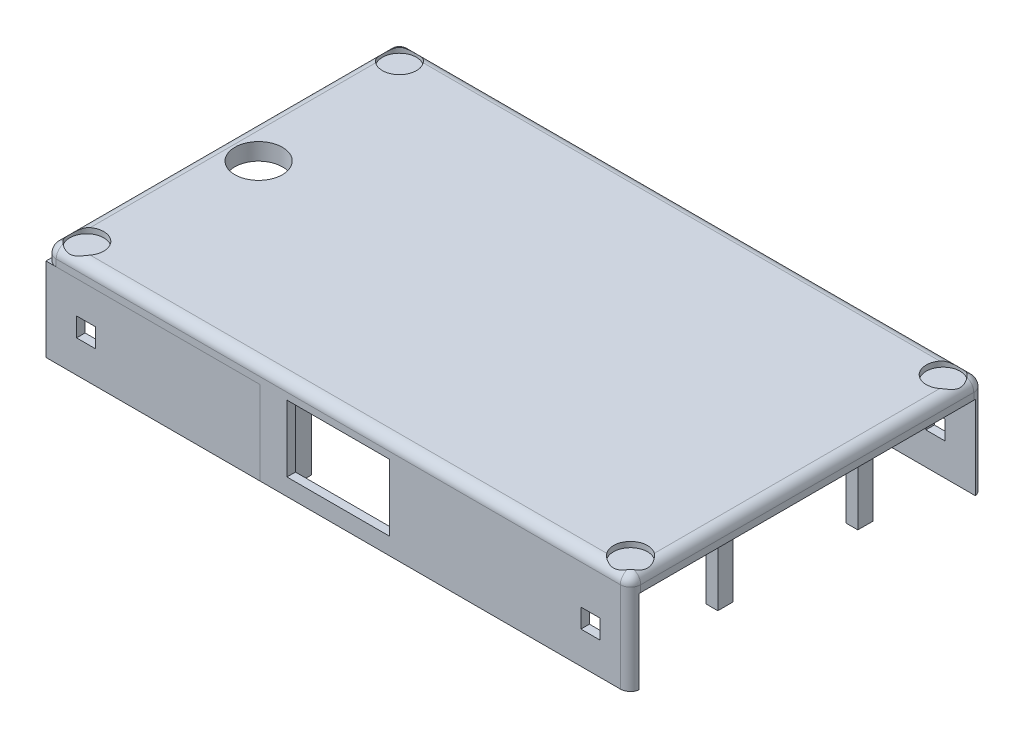
SolidWorks part; units mm, degrees
ref_plane "Plano frontal" through (0, 0, 0) normal (0, 0, 1) x (1, 0, 0)
ref_plane "Plano superior" through (0, 0, 0) normal (0, 1, 0) x (1, 0, 0)
ref_plane "Plano direito" through (0, 0, 0) normal (1, 0, 0) x (0, 0, -1)
sketch "Esboço1" plane through (0, 0, 0) normal (0, 1, 0) x (1, 0, 0)
  line L1 (-102.6129, 52.2382) -> (69.3871, 52.2382)
  line L2 (-102.6129, 52.2382) -> (-102.6129, -51.7618)
  line L3 (-102.6129, -51.7618) -> (69.3871, -51.7618)
  line L4 (69.3871, 52.2382) -> (69.3871, -51.7618)
extrude "Ressalto-extrusão1" add sketch "Esboço1" along normal blind 5
sketch "Esboço6" plane through (0, 0, 51.7618) normal (0, 0, 1) x (1, 0, 0)
  line L1 (-102.6129, 0) -> (-39.6029, 0)
  line L2 (-102.6129, 0) -> (-102.6129, -24.6)
  line L3 (-102.6129, -24.6) -> (-39.6029, -24.6)
  line L4 (-39.6029, 0) -> (-39.6029, -24.6)
extrude "Ressalto-extrusão3" add sketch "Esboço6" against normal blind 2.5 separate body
sketch "Esboço9" plane through (0, 0, 49.2618) normal (0, 0, -1) x (-1, 0, 0)
  line L1 (93.6129, -9.5) -> (88.0129, -9.5)
  line L2 (93.6129, -9.5) -> (93.6129, -15.1)
  line L3 (93.6129, -15.1) -> (88.0129, -15.1)
  line L4 (88.0129, -9.5) -> (88.0129, -15.1)
  line L6 (39.6029, 0) -> (102.6129, 0) construction
  line L7 (102.6129, -24.6) -> (39.6029, -24.6) construction
  line L8 (102.6129, 0) -> (102.6129, -24.6) construction
  dimension "D1" = 9.5
  dimension "D2" = 9
  dimension "D3" = 9.5
extrude "Corte-extrusão1" cut sketch "Esboço9" against normal blind 5
sketch "Esboço10" plane through (0, 0, -52.2382) normal (0, 0, -1) x (-1, 0, 0)
  line L1 (102.6129, 0) -> (39.6129, 0)
  line L2 (102.6129, 0) -> (102.6129, -24.6)
  line L3 (102.6129, -24.6) -> (39.6129, -24.6)
  line L4 (39.6129, 0) -> (39.6129, -24.6)
extrude "Ressalto-extrusão4" add sketch "Esboço10" against normal blind 2.5 separate body
sketch "Esboço11" plane through (0, 0, -49.7382) normal (0, 0, 1) x (1, 0, 0)
  line L1 (-102.6129, 0) -> (69.3871, 0) construction
  line L2 (-88.0129, -15.1) -> (-93.6129, -15.1)
  line L3 (-88.0129, -15.1) -> (-88.0129, -9.5)
  line L4 (-88.0129, -9.5) -> (-93.6129, -9.5)
  line L14 (-102.6129, -24.6) -> (-102.6129, 0) construction
  line L15 (-93.6129, -15.1) -> (-93.6129, -9.5)
  line L16 (-39.6129, -24.6) -> (-102.6129, -24.6) construction
  dimension "D1" = 9
  dimension "D2" = 9.5
  dimension "D3" = 9.5
extrude "Corte-extrusão2" cut sketch "Esboço11" against normal blind 5
sketch "Esboço12" plane through (0, 0, -52.2382) normal (0, 0, -1) x (-1, 0, 0)
  line L1 (-69.3871, 0) -> (-6.3871, 0)
  line L2 (-69.3871, 0) -> (-69.3871, -24.6)
  line L3 (-69.3871, -24.6) -> (-6.3871, -24.6)
  line L4 (-6.3871, 0) -> (-6.3871, -24.6)
extrude "Ressalto-extrusão5" add sketch "Esboço12" against normal blind 2.5 separate body
sketch "Esboço15" plane through (0, 0, 51.7618) normal (0, 0, 1) x (1, 0, 0)
  line L1 (69.3871, 0) -> (6.3871, 0)
  line L2 (69.3871, 0) -> (69.3871, -24.6)
  line L3 (69.3871, -24.6) -> (6.3871, -24.6)
  line L4 (6.3871, 0) -> (6.3871, -24.6)
extrude "Ressalto-extrusão6" add sketch "Esboço15" against normal blind 2.5 separate body
sketch "Esboço18" plane through (0, 0, -52.2382) normal (0, 0, -1) x (-1, 0, 0)
  line L0 (-69.3871, -24.6) -> (-6.3871, -24.6) construction
  line L1 (-54.7871, -15.1) -> (-60.3871, -15.1)
  line L2 (-54.7871, -15.1) -> (-54.7871, -9.5)
  line L3 (-54.7871, -9.5) -> (-60.3871, -9.5)
  line L4 (-60.3871, -15.1) -> (-60.3871, -9.5)
  line L5 (-6.3871, 0) -> (-69.3871, 0) construction
  line L6 (-69.3871, 0) -> (-69.3871, -24.6) construction
  dimension "D1" = 9.5
  dimension "D2" = 9.5
  dimension "D3" = 9
extrude "Corte-extrusão5" cut sketch "Esboço18" against normal blind 10
sketch "Esboço19" plane through (0, 0, 51.7618) normal (0, 0, 1) x (1, 0, 0)
  line L1 (60.3871, -15.1) -> (54.7871, -15.1)
  line L2 (60.3871, -15.1) -> (60.3871, -9.5)
  line L3 (60.3871, -9.5) -> (54.7871, -9.5)
  line L4 (54.7871, -15.1) -> (54.7871, -9.5)
  line L5 (69.3871, 0) -> (6.3871, 0) construction
  line L6 (6.3871, -24.6) -> (69.3871, -24.6) construction
  line L7 (69.3871, -24.6) -> (69.3871, 0) construction
  point P4 (57.5871, -9.5)
  dimension "D1" = 9.5
  dimension "D2" = 9.5
  dimension "D3" = 9
extrude "Corte-extrusão6" cut sketch "Esboço19" against normal blind 10
sketch "Esboço20" plane through (0, 0, 51.7618) normal (0, 0, 1) x (1, 0, 0)
  line L1 (6.3871, 0) -> (-1.5129, 0)
  line L2 (6.3871, 0) -> (6.3871, -24.6)
  line L3 (6.3871, -24.6) -> (-1.5129, -24.6)
  line L4 (-1.5129, 0) -> (-1.5129, -24.6)
extrude "Ressalto-extrusão7" add sketch "Esboço20" against normal blind 2.5
sketch "Esboço21" plane through (0, 0, 51.7618) normal (0, 0, 1) x (1, 0, 0)
  line L1 (-39.6029, 0) -> (-31.7129, 0)
  line L2 (-39.6029, 0) -> (-39.6029, -24.6)
  line L3 (-39.6029, -24.6) -> (-31.7129, -24.6)
  line L4 (-31.7129, 0) -> (-31.7129, -24.6)
extrude "Ressalto-extrusão8" add sketch "Esboço21" against normal blind 2.5 separate body
sketch "Esboço25" plane through (0, 0, 0) normal (0, -1, 0) x (1, 0, 0)
  line L0 (69.3871, 49.2618) -> (-1.5129, 49.2618) construction
  line L2 (4.3071, 49.2618) -> (0.3871, 49.2618)
  line L3 (4.3071, 49.2618) -> (4.3071, 42.6618)
  line L4 (4.3071, 42.6618) -> (0.3871, 42.6618)
  line L5 (0.3871, 49.2618) -> (0.3871, 42.6618)
  dimension "D1" = 1.9
extrude "Ressalto-extrusão9" add sketch "Esboço25" along normal blind 24.6
sketch "Esboço27" plane through (0, 0, 0) normal (0, -1, 0) x (1, 0, 0)
  line L0 (-31.7129, 49.2618) -> (-39.6029, 49.2618) construction
  line L1 (-37.5329, 42.6618) -> (-33.6129, 42.6618)
  line L2 (-37.5329, 42.6618) -> (-37.5329, 49.2618)
  line L3 (-37.5329, 49.2618) -> (-33.6129, 49.2618)
  line L4 (-33.6129, 42.6618) -> (-33.6129, 49.2618)
  line L6 (-31.7129, 49.2618) -> (-31.7129, 51.7618) construction
  dimension "D1" = 0
  dimension "D2" = 1.9
extrude "Ressalto-extrusão10" add sketch "Esboço27" along normal blind 24.6
sketch "Esboço28" plane through (-31.7129, 0, 0) normal (1, 0, 0) x (0, 0, -1)
  line L0 (-51.7618, -24.6) -> (-51.7618, 0) construction
  line L1 (-49.2618, -24.6) -> (-51.7618, -24.6)
  line L2 (-49.2618, -24.6) -> (-49.2618, -19.6)
  line L3 (-49.2618, -19.6) -> (-51.7618, -19.6)
  line L4 (-51.7618, -24.6) -> (-51.7618, -19.6)
extrude "Ressalto-extrusão11" add sketch "Esboço28" along normal blind 30.6
sketch "Esboço29" plane through (0, 0, -52.2382) normal (0, 0, -1) x (-1, 0, 0)
  line L0 (-69.3871, 0) -> (102.6129, 0) construction
  line L1 (39.6129, -24.6) -> (31.7129, -24.6)
  line L2 (39.6129, -24.6) -> (39.6129, 0)
  line L3 (39.6129, 0) -> (31.7129, 0)
  line L4 (31.7129, -24.6) -> (31.7129, 0)
extrude "Ressalto-extrusão12" add sketch "Esboço29" against normal blind 2.5
sketch "Esboço30" plane through (0, 0, -52.2382) normal (0, 0, -1) x (-1, 0, 0)
  line L0 (-6.3871, -24.6) -> (-6.3871, 0) construction
  line L1 (-6.3871, -24.6) -> (1.5129, -24.6)
  line L2 (-6.3871, -24.6) -> (-6.3871, 0)
  line L3 (-6.3871, 0) -> (1.5129, 0)
  line L4 (1.5129, -24.6) -> (1.5129, 0)
  line L5 (-69.3871, 0) -> (31.7129, 0) construction
extrude "Ressalto-extrusão13" add sketch "Esboço30" against normal blind 2.5
sketch "Esboço31" plane through (0, 0, 0) normal (0, -1, 0) x (1, 0, 0)
  line L0 (-102.6129, -49.7382) -> (-31.7129, -49.7382) construction
  line L1 (-37.5329, -49.7382) -> (-33.6129, -49.7382)
  line L2 (-37.5329, -49.7382) -> (-37.5329, -43.1382)
  line L3 (-37.5329, -43.1382) -> (-33.6129, -43.1382)
  line L4 (-33.6129, -49.7382) -> (-33.6129, -43.1382)
  dimension "D1" = 1.9
extrude "Ressalto-extrusão14" add sketch "Esboço31" along normal blind 24.6
sketch "Esboço32" plane through (0, 0, 0) normal (0, -1, 0) x (1, 0, 0)
  line L0 (-1.5129, -49.7382) -> (69.3871, -49.7382) construction
  line L1 (4.3071, -49.7382) -> (0.3871, -49.7382)
  line L2 (4.3071, -49.7382) -> (4.3071, -45.6382)
  line L3 (4.3071, -45.6382) -> (0.3871, -45.6382)
  line L4 (0.3871, -49.7382) -> (0.3871, -45.6382)
  line L5 (-1.5129, -49.7382) -> (-1.5129, -52.2382) construction
  dimension "D1" = 4.1
  dimension "D2" = 1.9
extrude "Ressalto-extrusão15" add sketch "Esboço32" along normal blind 24.6
sketch "Esboço34" plane through (0, 0, -52.2382) normal (0, 0, -1) x (-1, 0, 0)
  line L0 (1.5129, -24.6) -> (1.5129, 0) construction
  line L1 (31.7129, -24.6) -> (1.5129, -24.6)
  line L2 (31.7129, -24.6) -> (31.7129, -19.6)
  line L3 (31.7129, -19.6) -> (1.5129, -19.6)
  line L4 (1.5129, -24.6) -> (1.5129, -19.6)
extrude "Ressalto-extrusão16" add sketch "Esboço34" against normal blind 2.5
sketch "Esboço44" plane through (0, 5, 0) normal (0, 1, 0) x (1, 0, 0)
  line L1 (-102.6129, 52.2382) -> (-102.6129, -51.7618) construction
  line L3 (-102.6129, -51.7618) -> (69.3871, -51.7618) construction
  circle A0 centre (-96.6129, -45.7618) radius 5
  dimension "D1" = 6
  dimension "D2" = 6
sketch "Esboço47" plane through (0, 5, 0) normal (0, 1, 0) x (1, 0, 0)
  line L0 (-102.6129, 52.2382) -> (-102.6129, -51.7618) construction
  line L1 (69.3871, 52.2382) -> (-102.6129, 52.2382) construction
  circle A0 centre (-96.6129, 46.2382) radius 5
  dimension "D1" = 6
  dimension "D2" = 6
sketch "Esboço48" plane through (0, 5, 0) normal (0, 1, 0) x (1, 0, 0)
  line L0 (-102.6129, -51.7618) -> (69.3871, -51.7618) construction
  line L1 (69.3871, -51.7618) -> (69.3871, 52.2382) construction
  circle A0 centre (63.3871, -45.7618) radius 5
  dimension "D1" = 6
  dimension "D2" = 6
sketch "Esboço49" plane through (0, 5, 0) normal (0, 1, 0) x (1, 0, 0)
  line L0 (69.3871, 52.2382) -> (-102.6129, 52.2382) construction
  line L1 (69.3871, -51.7618) -> (69.3871, 52.2382) construction
  circle A0 centre (63.3871, 46.2382) radius 5
  dimension "D1" = 6
  dimension "D2" = 6
fillet "Filete3" radius 3 1 edges at (-16.6129, 5, 51.7618)
fillet "Filete4" radius 3 3 edges at (69.3871, -11.3, 51.7618) (69.3871, 4.1213, 50.8831) (69.3871, 5, -1.7382)
fillet "Filete5" radius 3 3 edges at (69.3871, -11.3, -52.2382) (68.5085, 4.1213, -52.2382) (-18.1129, 5, -52.2382)
fillet "Filete6" radius 3 5 edges at (-102.6129, -11.3, -52.2382) (-102.6129, 4.1213, -51.3595) (-102.6129, 1, 51.7618) (-102.6129, 4.1213, 50.8831) (-102.6129, 5, -0.2382)
sketch "Esboço53" plane through (0, 0, 0) normal (0, -1, 0) x (1, 0, 0)
  circle A0 centre (-91.8141, 0) radius 7
extrude "Corte-extrusão12" cut sketch "Esboço53" against normal blind 134
sketch "Esboço55" plane through (0, 0, 0) normal (0, -1, 0) x (1, 0, 0)
  line L1 (61.7667, 17.4581) -> (65.2667, 17.4581)
  line L2 (61.7667, 17.4581) -> (61.7667, 21.9581)
  line L3 (61.7667, 21.9581) -> (65.2667, 21.9581)
  line L4 (65.2667, 17.4581) -> (65.2667, 21.9581)
extrude "Ressalto-extrusão29" add sketch "Esboço55" along normal blind 20.1
sketch "Esboço57" plane through (0, 0, 0) normal (0, -1, 0) x (1, 0, 0)
  line L0 (69.3871, 48.7618) -> (69.3871, -49.2382) construction
  line L1 (65.2671, -19.2382) -> (61.7671, -19.2382)
  line L2 (65.2671, -19.2382) -> (65.2671, -23.7382)
  line L3 (65.2671, -23.7382) -> (61.7671, -23.7382)
  line L4 (61.7671, -19.2382) -> (61.7671, -23.7382)
  line L5 (69.3452, -49.7382) -> (4.3071, -49.7382) construction
  dimension "D1" = 4.12
  dimension "D2" = 26
extrude "Ressalto-extrusão30" add sketch "Esboço57" along normal blind 20.1
sketch "Esboço58" plane through (0, 0, 0) normal (0, -1, 0) x (-1, 0, 0)
  line L0 (-61.7667, -17.4581) -> (-65.2667, -17.4581) construction
  line L1 (-65.2671, -17.4581) -> (-61.7671, -17.4581)
  line L2 (-65.2671, -17.4581) -> (-65.2671, 19.2398)
  line L3 (-65.2671, 19.2398) -> (-61.7671, 19.2398)
  line L4 (-61.7671, -17.4581) -> (-61.7671, 19.2398)
  line L5 (-69.3871, -48.7618) -> (-69.3871, 49.2382) construction
  dimension "D1" = 4.12
extrude "Ressalto-extrusão31" add sketch "Esboço58" along normal blind 4 contours L2 L3 L4 L1
extrude "Corte-extrusão13" cut sketch "Esboço49" against normal blind 1.6 contours A0
extrude "Corte-extrusão14" cut sketch "Esboço47" against normal blind 1.6 contours A0
extrude "Corte-extrusão15" cut sketch "Esboço44" against normal blind 1.6 contours A0
extrude "Corte-extrusão16" cut sketch "Esboço48" against normal blind 1.6 contours A0
